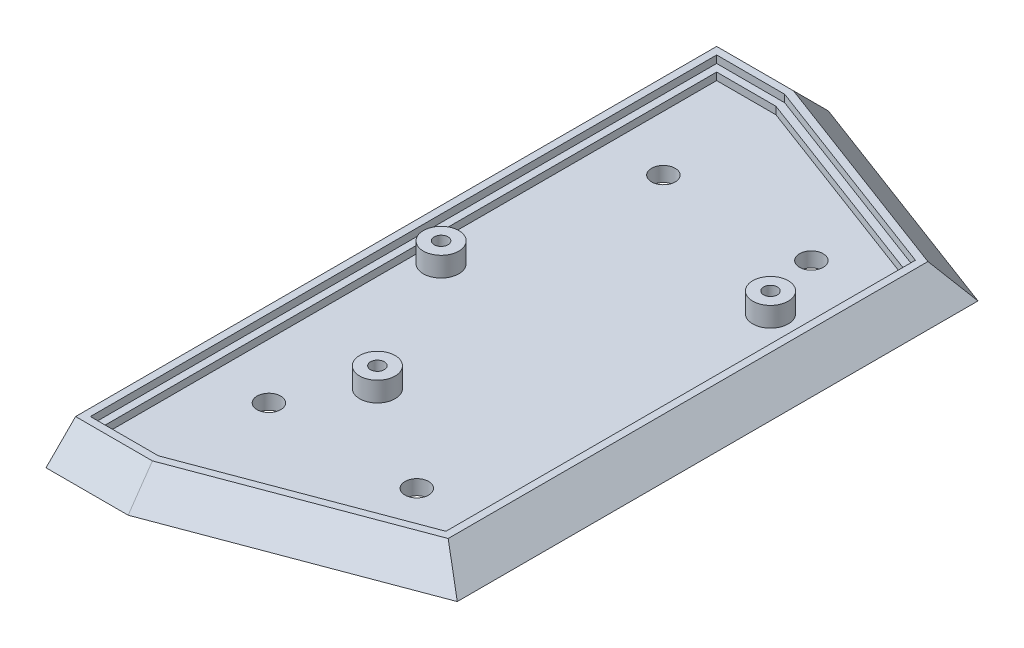
SolidWorks part; units mm, degrees
ref_plane "Front Plane" through (0, 0, 0) normal (0, 0, 1) x (1, 0, 0)
ref_plane "Top Plane" through (0, 0, 0) normal (0, 1, 0) x (1, 0, 0)
ref_plane "Right Plane" through (0, 0, 0) normal (1, 0, 0) x (0, 0, -1)
sketch "Sketch2" plane through (0, 0, 0) normal (0, 1, 0) x (1, 0, 0)
  line L0 (153.17, 0) -> (183.9921, 11.5583)
  line L1 (183.9921, 11.5583) -> (183.9921, 78.6117)
  line L2 (153.17, 90.17) -> (142.5901, 90.17)
  line L3 (183.9921, 78.6117) -> (153.17, 90.17)
  line L4 (142.5901, 0) -> (153.17, 0)
  line L5 (142.5901, 0) -> (142.5901, 90.17)
  dimension "D1" = 90.17
ref_plane "Plane1" through (0, 3.81, 0) normal (0, 1, 0) x (1, 0, 0)
sketch "Sketch3" plane through (0, 3.81, 0) normal (0, 1, 0) x (1, 0, 0)
  line L5 (180.1821, 45.085) -> (142.5901, 45.085) construction
  line L6 (152.4791, 3.81) -> (152.4791, 86.36) construction
  line L7 (142.5901, 3.81) -> (142.5901, 86.36)
  line L10 (152.4791, 86.36) -> (142.5901, 86.36)
  line L11 (180.1821, 75.9714) -> (152.4791, 86.36)
  line L12 (180.1821, 14.1986) -> (180.1821, 75.9714)
  line L13 (142.5901, 3.81) -> (152.4791, 3.81)
  line L14 (152.4791, 3.81) -> (180.1821, 14.1986)
  line L15 (152.4791, 86.36) -> (142.5901, 86.36)
  line L16 (180.1821, 75.9714) -> (152.4791, 86.36)
  line L17 (180.1821, 14.1986) -> (180.1821, 75.9714)
  line L18 (142.5901, 3.81) -> (152.4791, 3.81)
  line L19 (152.4791, 3.81) -> (180.1821, 14.1986)
  dimension "D1" = 3.81
loft "Loft3" add profiles "Sketch2", "Sketch3"
sketch "Sketch14" plane through (0, 3.81, 0) normal (0, 1, 0) x (1, 0, 0)
  line L12 (178.2771, 74.6512) -> (152.1337, 84.455)
  line L13 (152.1337, 84.455) -> (144.4951, 84.455)
  line L14 (144.4951, 84.455) -> (144.4951, 5.715)
  line L15 (144.4951, 5.715) -> (152.1337, 5.715)
  line L16 (152.1337, 5.715) -> (178.2771, 15.5188)
  line L17 (178.2771, 15.5188) -> (178.2771, 74.6512)
  line L18 (178.2771, 74.6512) -> (152.1337, 84.455)
  line L19 (152.1337, 84.455) -> (144.4951, 84.455)
  line L20 (144.4951, 84.455) -> (144.4951, 5.715)
  line L21 (144.4951, 5.715) -> (152.1337, 5.715)
  line L22 (152.1337, 5.715) -> (178.2771, 15.5188)
  line L23 (178.2771, 15.5188) -> (178.2771, 74.6512)
  dimension "D1" = 1.905
extrude "Cut-Extrude4" cut sketch "Sketch14" against normal blind 1.905
sketch "Sketch15" plane through (0, 1.905, 0) normal (0, 1, 0) x (1, 0, 0)
  line L0 (144.4951, 84.455) -> (144.4951, 5.715) construction
  line L1 (145.1301, 26.3652) -> (175.8641, 26.3652)
  line L2 (145.1301, 26.3652) -> (145.1301, 63.8048)
  line L3 (145.1301, 63.8048) -> (175.8641, 63.8048)
  line L4 (175.8641, 26.3652) -> (175.8641, 63.8048)
  line L5 (142.5901, 86.36) -> (142.5901, 3.81) construction
  circle A0 centre (173.9591, 61.9252) radius 2.286
  circle A1 centre (147.1621, 46.3042) radius 2.286
  circle A2 centre (156.9919, 28.2702) radius 2.286
  point P4 (145.1301, 45.085)
  point P5 (160.4971, 63.8048)
  point P6 (175.8641, 45.085)
  point P7 (144.4951, 45.085)
  dimension "D5" = 4.572
  dimension "D6" = 4.572
  dimension "D7" = 4.572
  dimension "D10" = 28.702
  dimension "D11" = 19.939
  dimension "D12" = 1.905
  dimension "D13" = 35.56
  dimension "D2" = 0
  dimension "D3" = 30.734
  dimension "D4" = 37.4396
  dimension "D8" = 18.8722
  dimension "D9" = 1.905
  dimension "D14" = 2.54
extrude "Boss-Extrude3" add sketch "Sketch15" along normal blind 2.54 contours L2 A1 | L2 A1 | L4 A0 | L3 A0 | L4 A0 L3 | L1 A2 | L1 A2
sketch "Sketch17" plane through (0, 4.445, 0) normal (0, 1, 0) x (1, 0, 0)
  circle A0 centre (156.9919, 28.2702) radius 0.889
  circle A1 centre (147.1621, 46.3042) radius 0.889
  circle A2 centre (173.9591, 61.9252) radius 0.889
extrude "Cut-Extrude5" cut sketch "Sketch17" against normal blind 3.81
sketch "Sketch18" plane through (0, 3.81, 0) normal (0, 1, 0) x (1, 0, 0)
  line L6 (178.2771, 15.5188) -> (178.2771, 74.6512)
  line L7 (178.2771, 74.6512) -> (152.1337, 84.455)
  line L8 (152.1337, 84.455) -> (144.4951, 84.455)
  line L9 (144.4951, 84.455) -> (144.4951, 5.715)
  line L10 (144.4951, 5.715) -> (152.1337, 5.715)
  line L11 (152.1337, 5.715) -> (178.2771, 15.5188)
  line L12 (178.2771, 15.5188) -> (178.2771, 74.6512)
  line L13 (178.2771, 74.6512) -> (152.1337, 84.455)
  line L14 (152.1337, 84.455) -> (144.4951, 84.455)
  line L15 (144.4951, 84.455) -> (144.4951, 5.715)
  line L16 (144.4951, 5.715) -> (152.1337, 5.715)
  line L17 (152.1337, 5.715) -> (178.2771, 15.5188)
  line L24 (179.2296, 14.8587) -> (179.2296, 75.3113)
  line L25 (179.2296, 75.3113) -> (152.3064, 85.4075)
  line L26 (152.3064, 85.4075) -> (143.5426, 85.4075)
  line L27 (143.5426, 85.4075) -> (143.5426, 4.7625)
  line L28 (143.5426, 4.7625) -> (152.3064, 4.7625)
  line L29 (152.3064, 4.7625) -> (179.2296, 14.8587)
  line L30 (179.2296, 14.8587) -> (179.2296, 75.3113)
  line L31 (179.2296, 75.3113) -> (152.3064, 85.4075)
  line L32 (152.3064, 85.4075) -> (143.5426, 85.4075)
  line L33 (143.5426, 85.4075) -> (143.5426, 4.7625)
  line L34 (143.5426, 4.7625) -> (152.3064, 4.7625)
  line L35 (152.3064, 4.7625) -> (179.2296, 14.8587)
  dimension "D1" = 0
  dimension "D2" = 0.9525
extrude "Cut-Extrude6" cut sketch "Sketch18" against normal blind 0.9525
sketch "Sketch19" plane through (142.5901, 0, 0) normal (-1, 0, 0) x (0, 0, 1)
  line L0 (-84.455, 1.905) -> (-5.715, 1.905) construction
  line L1 (-84.455, 1.905) -> (-5.715, 1.905)
  line L2 (-5.715, 1.905) -> (-5.715, 2.8575) construction
  line L3 (-5.715, 1.905) -> (-5.715, 2.8575)
  line L4 (-86.36, 3.81) -> (-3.81, 3.81) construction
  line L5 (-20.3018, 3.81) -> (-15.0042, 3.81)
  line L6 (-14.7138, 3.81) -> (-9.4162, 3.81)
  line L7 (-20.462, 3.81) -> (-24.75, 3.81)
  arc A0 (-20.3018, 3.81) -> (-15.0042, 3.81) centre (-17.653, 4.699) ccw
  arc A1 (-14.7138, 3.81) -> (-9.4162, 3.81) centre (-12.065, 4.699) ccw
  arc A2 (-24.75, 3.81) -> (-20.462, 3.81) centre (-22.606, 4.064) ccw
  dimension "D1" = 5.588
  dimension "D2" = 5.588
  dimension "D6" = 2.159
  dimension "D3" = 5.588
  dimension "D4" = 2.794
  dimension "D5" = 6.35
  dimension "D7" = 4.953
sketch "Sketch20" plane through (0, 1.905, 0) normal (0, 1, 0) x (1, 0, 0)
  line L0 (151.6731, 84.455) -> (152.1337, 84.455)
  line L1 (144.4951, 5.715) -> (152.1337, 5.715) construction
  line L2 (178.2771, 45.085) -> (144.4951, 45.085) construction
  line L3 (178.2771, 15.5188) -> (178.2771, 74.6512) construction
  line L4 (144.4951, 84.455) -> (144.4951, 5.715) construction
  line L5 (152.1337, 5.715) -> (178.2771, 15.5188) construction
  line L6 (152.1337, 5.715) -> (178.2771, 15.5188) construction
  line L7 (144.4951, 5.715) -> (152.1337, 5.715) construction
  line L8 (178.2771, 15.5188) -> (178.2771, 17.279)
  line L9 (152.1337, 5.715) -> (152.5649, 5.8767)
  line L10 (151.6731, 5.715) -> (152.1337, 5.715)
  line L11 (152.1337, 84.455) -> (152.5649, 84.2933)
  line L12 (176.6289, 75.2693) -> (178.2771, 74.6512)
  line L13 (178.2771, 72.891) -> (178.2771, 74.6512)
  line L14 (176.6289, 14.9007) -> (178.2771, 15.5188)
  arc A0 (152.5649, 5.8767) -> (151.6731, 5.715) centre (151.6731, 8.255) ccw
  arc A1 (178.2771, 17.279) -> (176.6289, 14.9007) centre (175.7371, 17.279) ccw
  arc A2 (152.5649, 84.2933) -> (151.6731, 84.455) centre (151.6731, 81.915) cw
  arc A3 (178.2771, 72.891) -> (176.6289, 75.2693) centre (175.7371, 72.891) cw
  dimension "D1" = 5.08
  dimension "D3" = 2.54
  dimension "D4" = 5.08
  dimension "D5" = 2.54
  dimension "D2" = 2.54
  dimension "D6" = 2.54
sketch "Sketch22" plane through (0, 1.905, 0) normal (0, 1, 0) x (1, 0, 0)
  line L0 (178.2771, 45.085) -> (131.5292, 45.085) construction
  line L1 (170.6571, 19.685) -> (151.6071, 19.685)
  line L2 (170.6571, 19.685) -> (170.6571, 70.485)
  line L3 (170.6571, 70.485) -> (151.6071, 70.485)
  line L4 (151.6071, 19.685) -> (151.6071, 70.485)
  line L5 (178.2771, 15.5188) -> (178.2771, 74.6512) construction
  line L6 (183.9921, 11.5583) -> (183.9921, 78.6117) construction
  circle A0 centre (151.6071, 19.685) radius 1.524
  circle A1 centre (170.6571, 19.685) radius 1.524
  circle A2 centre (170.6571, 70.485) radius 1.524
  circle A3 centre (151.6071, 70.485) radius 1.524
  dimension "D1" = 50.8
  dimension "D2" = 19.05
  dimension "D3" = 13.335
  dimension "D4" = 25.4
extrude "Cut-Extrude9" cut sketch "Sketch22" against normal through all contours L1 A1 L2 | L2 A1 L1 | L4 A0 L1 | L1 A0 L4 | L2 A2 L3 | L3 A2 L2 | L3 A3 L4 | L4 A3 L3
